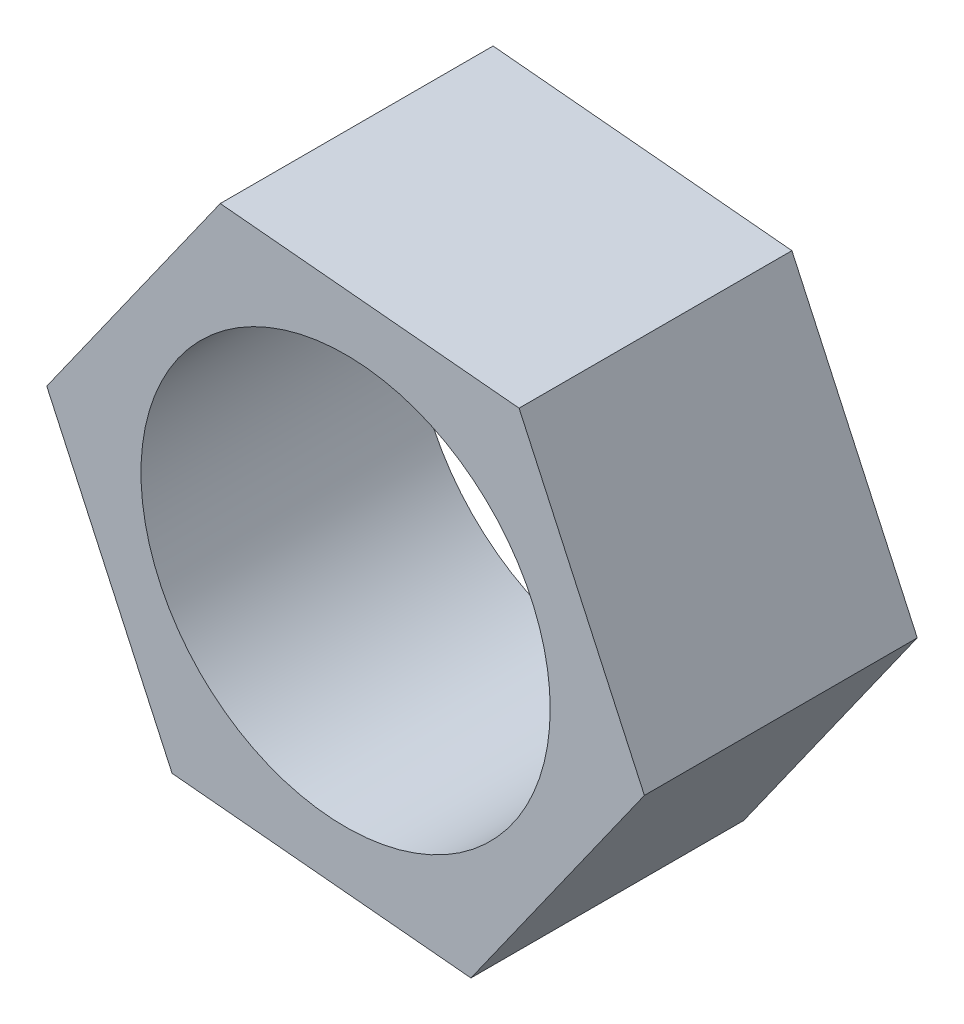
SolidWorks part; units mm, degrees
ref_plane "Plano frontal" through (0, 0, 0) normal (0, 0, 1) x (1, 0, 0)
ref_plane "Plano superior" through (0, 0, 0) normal (0, 1, 0) x (1, 0, 0)
ref_plane "Plano direito" through (0, 0, 0) normal (1, 0, 0) x (0, 0, -1)
sketch "Esboço1" plane through (0, 0, 0) normal (0, 0, 1) x (1, 0, 0)
  line L1 (6.359, 8.9757) -> (-4.5937, 9.9949)
  line L2 (-4.5937, 9.9949) -> (-10.9527, 1.0192)
  line L3 (-10.9527, 1.0192) -> (-6.359, -8.9757)
  line L4 (-6.359, -8.9757) -> (4.5937, -9.9949)
  line L5 (4.5937, -9.9949) -> (10.9527, -1.0192)
  line L6 (10.9527, -1.0192) -> (6.359, 8.9757)
  circle A0 centre (0, 0) radius 9.5263 construction
  circle A1 centre (0, 0) radius 7.5
  dimension "D2" = 15
  dimension "D1" = 22
extrude "Ressalto-extrusão1" add sketch "Esboço1" along normal blind 10
